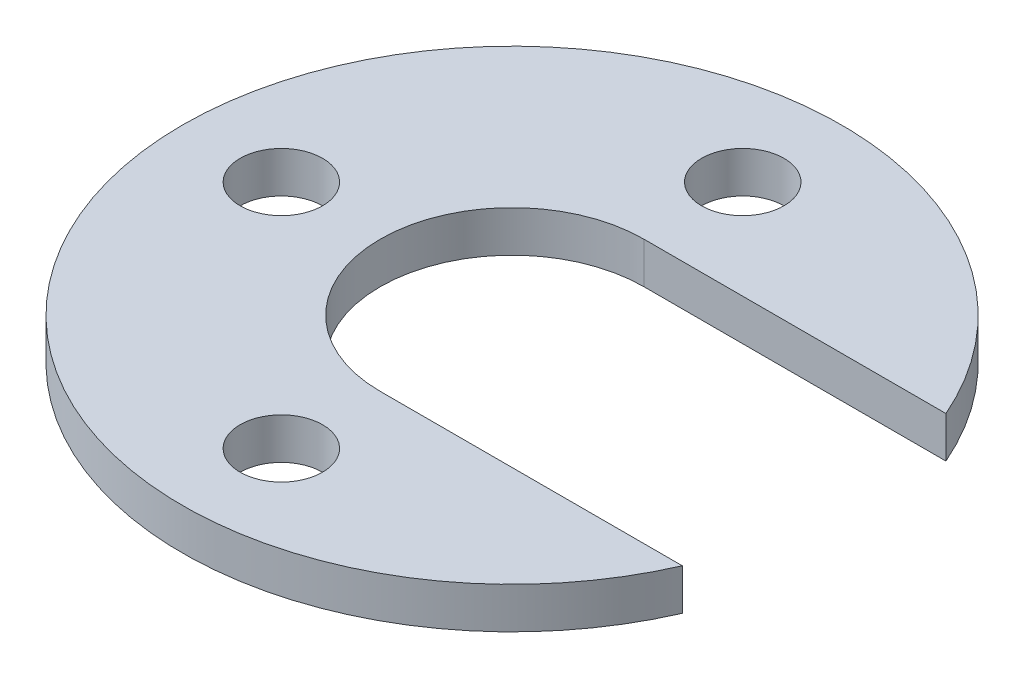
SolidWorks part; units mm, degrees
ref_plane "Front Plane" through (0, 0, 0) normal (0, 0, 1) x (1, 0, 0)
ref_plane "Top Plane" through (0, 0, 0) normal (0, 1, 0) x (1, 0, 0)
ref_plane "Right Plane" through (0, 0, 0) normal (1, 0, 0) x (0, 0, -1)
sketch "Sketch1" plane through (0, 0, 0) normal (0, 1, 0) x (1, 0, 0)
  line L0 (-49.2308, 0) -> (49.2308, 0) construction
  line L1 (0, -36.5385) -> (0, 36.5385) construction
  line L2 (0, 16) -> (36.6606, 16)
  line L3 (0, -16) -> (36.6606, -16)
  arc A0 (0, -16) -> (0, 16) centre (0, 0) cw
  arc A1 (36.6606, 16) -> (36.6606, -16) centre (0, 0) ccw
  circle A2 centre (0, 28) radius 5
  circle A3 centre (-28, 0) radius 5
  circle A4 centre (0, -28) radius 5
  point P4 (0, 0)
  point P8 (0, 0)
  dimension "D1" = 16
  dimension "D2" = 40
  dimension "D3" = 10
  dimension "D4" = 28
  dimension "D5" = 28
extrude "Boss-Extrude1" add sketch "Sketch1" along normal blind 5
